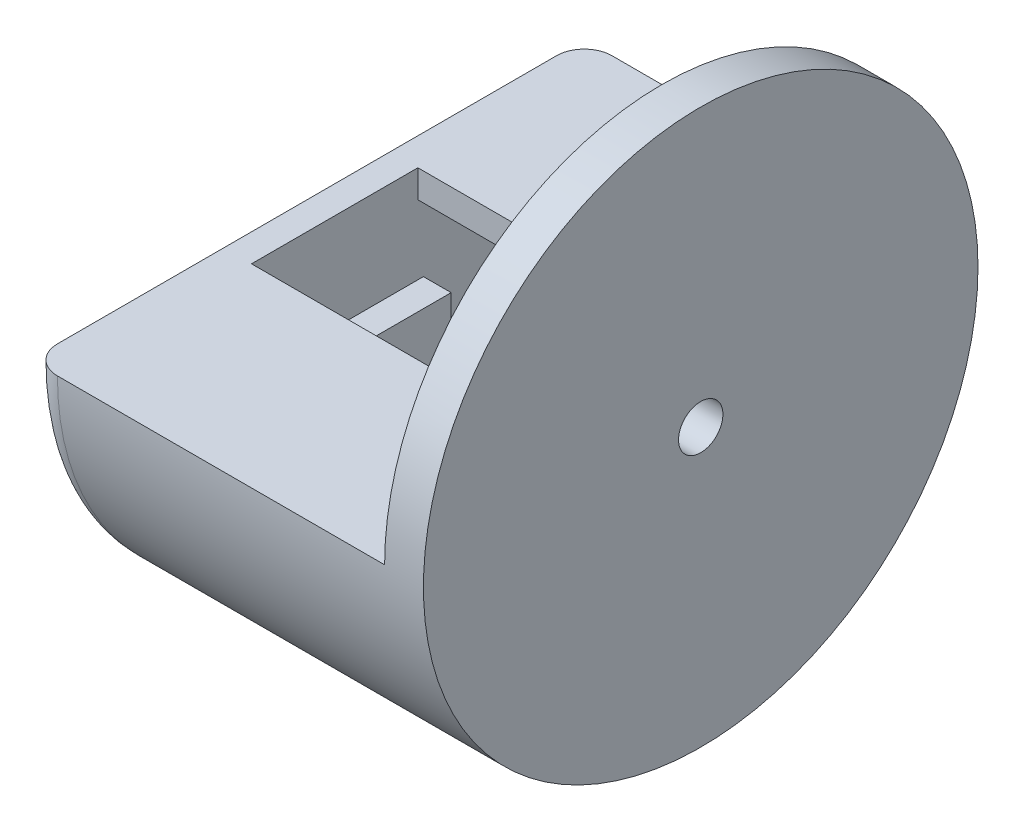
SolidWorks part; units mm, degrees
ref_plane "Front Plane" through (0, 0, 0) normal (0, 0, 1) x (1, 0, 0)
ref_plane "Top Plane" through (0, 0, 0) normal (0, 1, 0) x (1, 0, 0)
ref_plane "Right Plane" through (0, 0, 0) normal (1, 0, 0) x (0, 0, -1)
sketch "Sketch1" plane through (0, 0, 0) normal (0, 1, 0) x (1, 0, 0)
  line L1 (0, 0) -> (50, 0)
  line L2 (0, 0) -> (0, 20)
  line L3 (0, 20) -> (50, 20)
  line L4 (50, 0) -> (50, 20)
  dimension "D1" = 50
  dimension "D2" = 20
extrude "Boss-Extrude1" add sketch "Sketch1" along normal blind 10
sketch "Sketch3" plane through (0, 10, 0) normal (0, 1, 0) x (1, 0, 0)
  line L0 (0, 0) -> (50, 0) construction
  line L1 (0, 20) -> (5, 20)
  line L2 (0, 20) -> (0, 0)
  line L3 (0, 0) -> (5, 0)
  line L4 (5, 20) -> (5, 0)
  line L6 (50, 20) -> (45, 20)
  line L7 (50, 20) -> (50, 0)
  line L8 (50, 0) -> (45, 0)
  line L9 (45, 20) -> (45, 0)
  dimension "D1" = 5
  dimension "D2" = 5
extrude "Boss-Extrude2" add sketch "Sketch3" along normal blind 26
sketch "Sketch4" plane through (0, 0, -20) normal (0, 0, -1) x (-1, 0, 0)
  line L1 (-45, 36) -> (-60, 36)
  line L2 (-45, 36) -> (-45, 0)
  line L3 (-45, 0) -> (-60, 0)
  line L4 (-60, 36) -> (-60, 0)
  dimension "D1" = 15
extrude "Boss-Extrude3" add sketch "Sketch4" against normal blind 20
sketch "Sketch5" plane through (60, 0, 0) normal (1, 0, 0) x (0, 0, -1)
  line L0 (10, 0) -> (10, 47.5)
  line L1 (0, 0) -> (20, 0) construction
  line L3 (0, 36) -> (20, 36)
  line L4 (0, 36) -> (0, 47.5)
  line L5 (0, 47.5) -> (20, 47.5)
  line L6 (20, 36) -> (20, 47.5)
  circle A0 centre (10, 47.5) radius 10
  circle A1 centre (10, 47.5) radius 4
  line M4 (20, 36) -> (0, 36)
  dimension "D1" = 47.5
  dimension "D2" = 20
extrude "Boss-Extrude4" add sketch "Sketch5" against normal blind 7 contours A0 L0 L6 M4 | A1 L0 A0 L5 | A0 L4 L0 M4 | A1 L5 A0 L0 | A1 L5 A0
sketch "Sketch6" plane through (60, 0, 0) normal (1, 0, 0) x (0, 0, -1)
  circle A0 centre (10, 47.5) radius 50
  circle A1 centre (10, 47.5) radius 4
  dimension "D1" = 100
extrude "Boss-Extrude5" add sketch "Sketch6" against normal up to vertex
sketch "Sketch7" plane through (53, 0, 0) normal (-1, 0, 0) x (0, 0, 1)
  line L0 (-60, 47.5) -> (-55, 47.5)
  line L1 (35, 47.5) -> (40, 47.5)
  circle A0 centre (-10, 47.5) radius 50 construction
  arc A1 (-60, 47.5) -> (40, 47.5) centre (-10, 47.5) ccw
  arc A2 (-55, 47.5) -> (35, 47.5) centre (-10, 47.5) ccw
extrude "Boss-Extrude6" add sketch "Sketch7" along normal blind 64
sketch "Sketch8" plane through (-11, 0, 0) normal (-1, 0, 0) x (0, 0, 1)
  line L0 (-55, 47.5) -> (35, 47.5)
  arc A1 (-55, 47.5) -> (35, 47.5) centre (-10, 47.5) ccw
extrude "Boss-Extrude7" add sketch "Sketch8" against normal blind 5
fillet "Fillet1" radius 5 1 edges at (-11, -2.5, -10)
sketch "Sketch9" plane through (0, 47.5, 0) normal (0, 1, 0) x (1, 0, 0)
  line L0 (53, 60) -> (53, -40) construction
  line L1 (-6, 55) -> (53, 55)
  line L2 (-6, 55) -> (-6, 25)
  line L3 (-6, 25) -> (53, 25)
  line L4 (53, 55) -> (53, 25)
  line L5 (-6, 10) -> (53, 10)
  line L6 (-6, -35) -> (-6, 55) construction
  line L7 (-6, -5) -> (53, -5)
  line L8 (53, -35) -> (53, -5)
  line L9 (-6, -35) -> (53, -35)
  line L10 (-6, -35) -> (-6, -5)
  line M14 (53, -35) -> (-6, -35)
  line M15 (-6, -35) -> (-6, 55)
  line M16 (-6, 55) -> (53, 55)
  dimension "D1" = 30
extrude "Boss-Extrude8" add sketch "Sketch9" against normal blind 5 contours L4 L3 M16 M15 | L8 L7 M14 M15
sketch "Sketch10" plane through (0, 0, -20) normal (0, 0, -1) x (-1, 0, 0)
  line L0 (-5, 36) -> (-5, 10) construction
  line L1 (-5, 36) -> (-45, 36)
  line L2 (-5, 36) -> (-5, 10)
  line L3 (-5, 10) -> (-45, 10)
  line L4 (-45, 36) -> (-45, 10)
  dimension "D1" = 26
  dimension "D2" = 40
